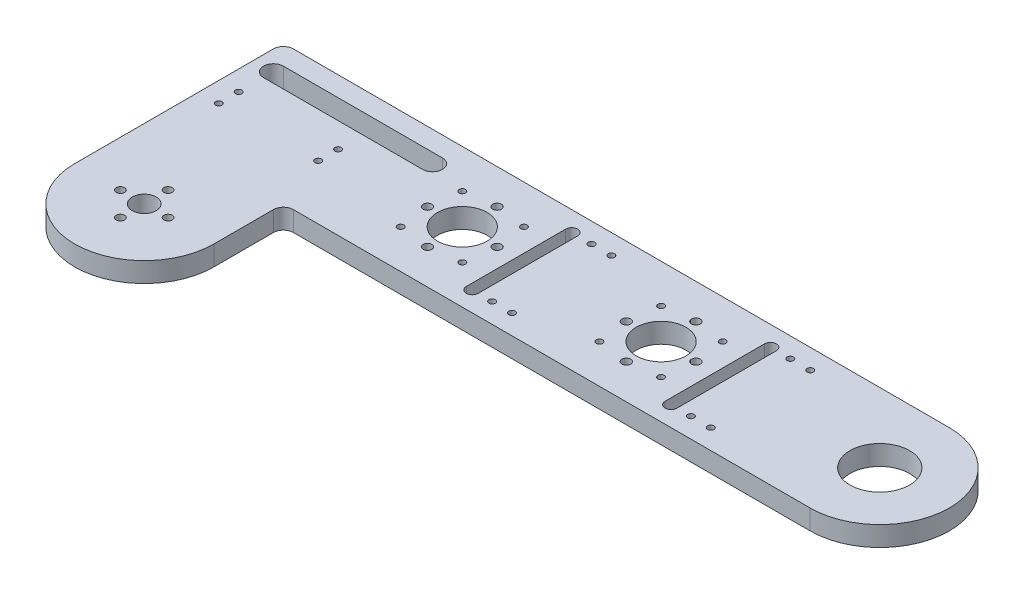
SolidWorks part; units mm, degrees
material "Acrylic (Medium-high impact)"
ref_plane "Front Plane" through (0, 0, 0) normal (0, 0, 1) x (1, 0, 0)
ref_plane "Top Plane" through (0, 0, 0) normal (0, 1, 0) x (1, 0, 0)
ref_plane "Right Plane" through (0, 0, 0) normal (1, 0, 0) x (0, 0, -1)
sketch "Sketch1" plane through (0, 0, 0) normal (0, 1, 0) x (1, 0, 0)
  line L0 (0, 0) -> (0, 70) construction
  line L1 (0, 70) -> (300, 70) construction
  line L2 (35, 0) -> (35, 35)
  line L3 (35, 35) -> (300, 35)
  line L4 (-35, 0) -> (-35, 105)
  line L5 (-35, 105) -> (300, 105)
  arc A0 (35, 0) -> (-35, 0) centre (0, 0) cw
  arc A1 (300, 35) -> (300, 105) centre (300, 70) ccw
  circle A2 centre (0, 0) radius 6
  circle A3 centre (300, 70) radius 15
  dimension "D5" = 30
  dimension "D6" = 12
  dimension "D1" = 300
  dimension "D2" = 70
  dimension "D3" = 35
  dimension "D4" = 35
extrude "Boss-Extrude1" add sketch "Sketch1" along normal mid plane 10
fillet "Fillet1" radius 5 2 edges at (-35, 0, -105) (35, 0, -35)
sketch "Sketch3" plane through (0, 5, 0) normal (0, 1, 0) x (1, 0, 0)
  circle A0 centre (0, -12) radius 2.1
  dimension "D1" = 12
  dimension "D2" = 4.2
extrude "Cut-Extrude1" cut sketch "Sketch3" against normal through all both and the other way through all
pattern_circular "CirPattern1" count 4 over 360 about axis through (0, 0, 0) along (0, 1, 0) of "Cut-Extrude1"
sketch "Sketch4" plane through (0, 5, 0) normal (0, 1, 0) x (1, 0, 0)
  line L0 (235, 105) -> (235, 35) construction
  line L1 (300, 105) -> (-30, 105) construction
  line L2 (40, 35) -> (300, 35) construction
  line L3 (-35, 100) -> (-35, 0) construction
  line L4 (230, 45) -> (240, 45) construction
  line L5 (230, 45) -> (230, 95) construction
  line L6 (230, 95) -> (240, 95) construction
  line L7 (240, 45) -> (240, 95) construction
  line L8 (230, 45) -> (240, 95) construction
  line L9 (230, 95) -> (240, 45) construction
  line L10 (35, 30) -> (35, 105) construction
  line L11 (35, 67.5) -> (-35, 67.5) construction
  line L12 (135, 105) -> (135, 35) construction
  line L13 (-25, 62.5) -> (25, 62.5) construction
  line L14 (-25, 62.5) -> (-25, 72.5) construction
  line L15 (-25, 72.5) -> (25, 72.5) construction
  line L16 (25, 62.5) -> (25, 72.5) construction
  line L17 (-25, 62.5) -> (25, 72.5) construction
  line L18 (-25, 72.5) -> (25, 62.5) construction
  line L19 (130, 45) -> (140, 45) construction
  line L20 (130, 45) -> (130, 95) construction
  line L21 (130, 95) -> (140, 95) construction
  line L22 (140, 45) -> (140, 95) construction
  line L23 (130, 45) -> (140, 95) construction
  line L24 (130, 95) -> (140, 45) construction
  circle A0 centre (230, 95) radius 1.6
  circle A1 centre (240, 95) radius 1.6
  circle A2 centre (230, 45) radius 1.6
  circle A3 centre (240, 45) radius 1.6
  circle A4 centre (-25, 72.5) radius 1.6
  circle A5 centre (25, 72.5) radius 1.6
  circle A6 centre (-25, 62.5) radius 1.6
  circle A7 centre (25, 62.5) radius 1.6
  circle A8 centre (130, 95) radius 1.6
  circle A9 centre (140, 95) radius 1.6
  circle A10 centre (130, 45) radius 1.6
  circle A11 centre (140, 45) radius 1.6
  circle A12 centre (300, 70) radius 15 construction
  point P6 (235, 70)
  point P22 (0, 67.5)
  point P33 (135, 70)
  dimension "D4" = 3.2
  dimension "D5" = 10
  dimension "D7" = 3.2
  dimension "D1" = 10
  dimension "D2" = 50
  dimension "D3" = 270
  dimension "D6" = 50
  dimension "D8" = 65
  dimension "D9" = 100
extrude "Cut-Extrude2" cut sketch "Sketch4" against normal through all both and the other way through all
sketch "Sketch5" plane through (0, 5, 0) normal (0, 1, 0) x (1, 0, 0)
  line L0 (-35, 70) -> (335, 70) construction
  line L1 (174.5, 85.5) -> (205.5, 85.5) construction
  line L2 (174.5, 85.5) -> (174.5, 54.5) construction
  line L3 (174.5, 54.5) -> (205.5, 54.5) construction
  line L4 (205.5, 85.5) -> (205.5, 54.5) construction
  line L5 (174.5, 85.5) -> (205.5, 54.5) construction
  line L6 (174.5, 54.5) -> (205.5, 85.5) construction
  line L7 (-35, 100) -> (-35, 0) construction
  line L8 (220, 105) -> (220, 35) construction
  line L9 (300, 105) -> (-30, 105) construction
  line L10 (40, 35) -> (300, 35) construction
  line L11 (220, 95) -> (220, 45) construction
  line L12 (223, 95) -> (223, 45)
  line L13 (217, 95) -> (217, 45)
  arc A0 (300, 35) -> (300, 105) centre (300, 70) ccw construction
  circle A1 centre (174.5, 85.5) radius 1.6
  circle A2 centre (174.5, 54.5) radius 1.6
  circle A3 centre (205.5, 54.5) radius 1.6
  circle A4 centre (205.5, 85.5) radius 1.6
  circle A5 centre (300, 70) radius 15 construction
  arc A6 (223, 95) -> (217, 95) centre (220, 95) ccw
  arc A7 (217, 45) -> (223, 45) centre (220, 45) ccw
  circle A8 centre (190, 70) radius 12.5
  point P0 (190, 70)
  point P26 (220, 70)
  dimension "D2" = 3.2
  dimension "D6" = 25
  dimension "D1" = 31
  dimension "D3" = 110
  dimension "D4" = 6
  dimension "D5" = 30
  dimension "D7" = 10
  dimension "D8" = 10
extrude "Cut-Extrude3" cut sketch "Sketch5" against normal through all both and the other way through all contours A8 | A4 | A1 | A2 | A3 | L13 A7 L12 A6
sketch "Sketch7" plane through (0, 5, 0) normal (0, 1, 0) x (1, 0, 0)
  circle A0 centre (190, 70) radius 17.5 construction
  circle A1 centre (190, 87.5) radius 2.2
  circle A2 centre (172.5, 70) radius 2.2
  circle A3 centre (190, 52.5) radius 2.2
  circle A4 centre (207.5, 70) radius 2.2
  dimension "D1" = 4.4
  dimension "D2" = 35
extrude "Cut-Extrude5" cut sketch "Sketch7" against normal through all
pattern_linear "LPattern1" count 2 spacing 100 along (-1, 0, 0) of "Cut-Extrude3", "Cut-Extrude5"
sketch "Sketch6" plane through (0, 5, 0) normal (0, 1, 0) x (1, 0, 0)
  line L0 (-25, 90) -> (55, 90) construction
  line L1 (-25, 95) -> (55, 95)
  line L2 (-25, 85) -> (55, 85)
  line L3 (-35, 100) -> (-35, 0) construction
  line L4 (300, 105) -> (-30, 105) construction
  arc A0 (-25, 95) -> (-25, 85) centre (-25, 90) ccw
  arc A1 (55, 85) -> (55, 95) centre (55, 90) ccw
  point P2 (15, 90)
  dimension "D1" = 10
  dimension "D2" = 10
  dimension "D3" = 10
  dimension "D4" = 90
extrude "Cut-Extrude4" cut sketch "Sketch6" against normal through all both and the other way through all
